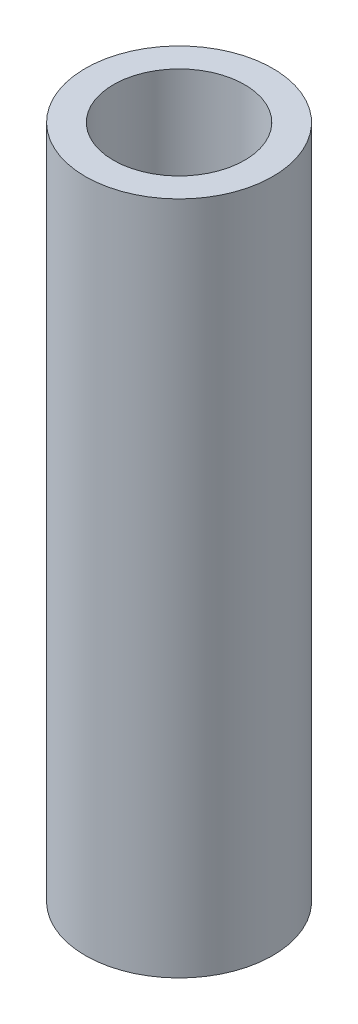
SolidWorks part; units mm, degrees
ref_plane "前视基准面" through (0, 0, 0) normal (0, 0, 1) x (1, 0, 0)
ref_plane "上视基准面" through (0, 0, 0) normal (0, 1, 0) x (1, 0, 0)
ref_plane "右视基准面" through (0, 0, 0) normal (1, 0, 0) x (0, 0, -1)
sketch "草图1" plane through (0, 0, 0) normal (0, 1, 0) x (1, 0, 0)
  circle A0 centre (0, 0) radius 10
  circle A1 centre (0, 0) radius 7
  dimension "D1" = 20
  dimension "D2" = 14
extrude "凸台-拉伸1" add sketch "草图1" along normal blind 72
